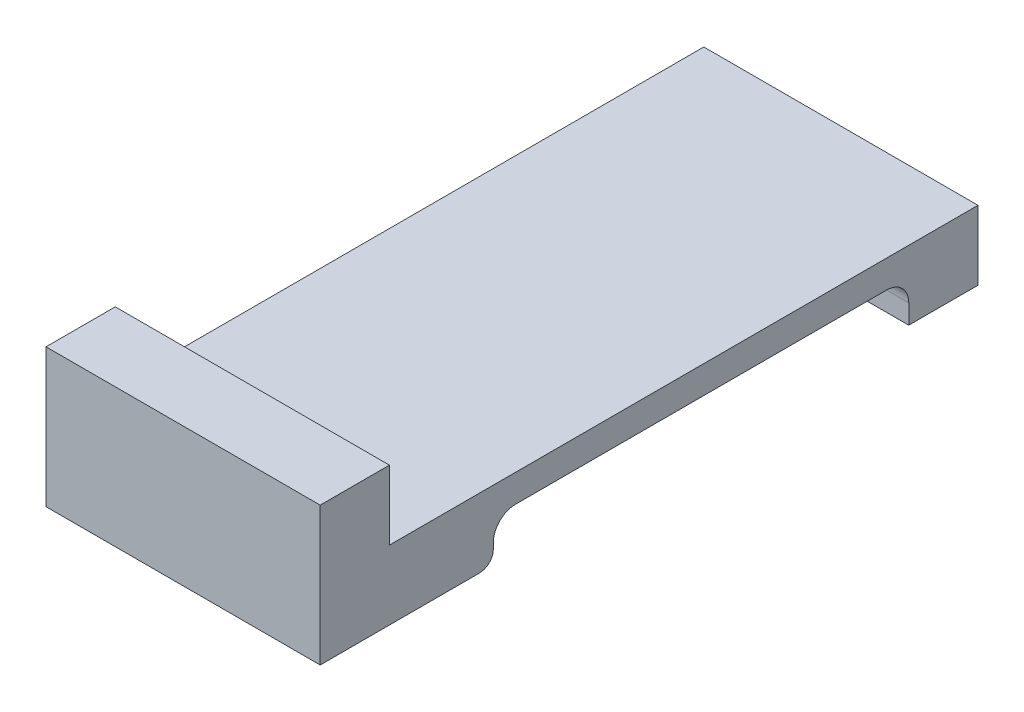
SolidWorks part; units mm, degrees
ref_plane "Front Plane" through (0, 0, 0) normal (0, 0, 1) x (1, 0, 0)
ref_plane "Top Plane" through (0, 0, 0) normal (0, 1, 0) x (1, 0, 0)
ref_plane "Right Plane" through (0, 0, 0) normal (1, 0, 0) x (0, 0, -1)
sketch "Sketch1" plane through (0, 0, 0) normal (1, 0, 0) x (0, 0, -1)
  line L1 (0, 0) -> (0, 6.35)
  line L2 (0, 6.35) -> (3.175, 6.35)
  line L3 (3.175, 6.35) -> (3.175, 3.175)
  line L4 (3.175, 3.175) -> (30.1625, 3.175)
  line L6 (0, 0) -> (7.3025, 0)
  line L7 (30.1625, 3.175) -> (30.1625, 0)
  line L8 (30.1625, 0) -> (26.9875, 0)
  line L9 (7.9375, 0.635) -> (7.9375, 0.889)
  line L10 (8.9535, 1.905) -> (25.9715, 1.905)
  line L11 (26.9875, 0.889) -> (26.9875, 0)
  arc A1 (25.9715, 1.905) -> (26.9875, 0.889) centre (25.9715, 0.889) cw
  arc A2 (7.9375, 0.889) -> (8.9535, 1.905) centre (8.9535, 0.889) cw
  arc A3 (7.3025, 0) -> (7.9375, 0.635) centre (7.3025, 0.635) ccw
  point P16 (-5.5864, 0)
  point P17 (-15.7313, 5.4842)
  point P18 (-10.9243, 6.35)
  point P19 (0, 0)
  point P22 (7.9375, 0)
  dimension "D6" = 1.016
  dimension "D9" = 0.635
  dimension "D1" = 4.7625
  dimension "D2" = 3.175
  dimension "D3" = 3.175
  dimension "D4" = 19.05
  dimension "D5" = 1.905
  dimension "D7" = 3.175
  dimension "D8" = 3.175
extrude "Boss-Extrude1" add sketch "Sketch1" along normal blind 12.573
